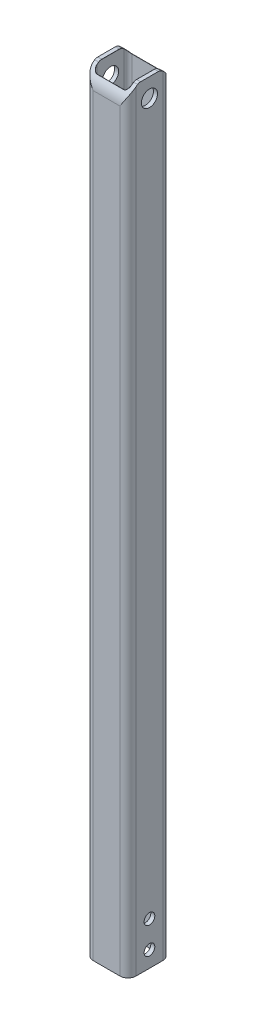
SolidWorks part; units mm, degrees
material "Plain Carbon Steel"
ref_plane "Front Plane" through (0, 0, 0) normal (0, 0, 1) x (1, 0, 0)
ref_plane "Top Plane" through (0, 0, 0) normal (0, 1, 0) x (1, 0, 0)
ref_plane "Right Plane" through (0, 0, 0) normal (1, 0, 0) x (0, 0, -1)
sketch3d "3DSketch1"
  line L0 (0, 0, 0) -> (0, 914.4, 0)
  dimension "D1" = 914.4
other "Tube (square) TS2X2X0.1875(1)"
ref_plane "Plane1" through (0, 0, 0) normal (0, 1, 0) x (1, 0, 0)
sketch "Sketch1" plane through (0, 0, 0) normal (0, 1, 0) x (1, 0, 0)
  line L0 (-15.875, -20.6375) -> (15.875, -20.6375)
  line L1 (-20.6375, -15.875) -> (-20.6375, 15.875)
  line L2 (15.875, 20.6375) -> (-15.875, 20.6375)
  line L3 (20.6375, 15.875) -> (20.6375, -15.875)
  line L4 (-15.875, -25.4) -> (15.875, -25.4)
  line L5 (-25.4, -15.875) -> (-25.4, 15.875)
  line L6 (15.875, 25.4) -> (-15.875, 25.4)
  line L7 (25.4, 15.875) -> (25.4, -15.875)
  line L8 (-25.4, 0) -> (-20.6375, 0) construction
  line L9 (-20.6375, 0) -> (20.6375, 0) construction
  line L10 (20.6375, 0) -> (25.4, 0) construction
  line L11 (0, 25.4) -> (0, 20.6375) construction
  line L12 (0, 20.6375) -> (0, -20.6375) construction
  line L13 (0, -20.6375) -> (0, -25.4) construction
  arc A0 (25.4, 15.875) -> (15.875, 25.4) centre (15.875, 15.875) ccw
  arc A1 (15.875, -25.4) -> (25.4, -15.875) centre (15.875, -15.875) ccw
  arc A2 (-25.4, -15.875) -> (-15.875, -25.4) centre (-15.875, -15.875) ccw
  arc A3 (-15.875, 25.4) -> (-25.4, 15.875) centre (-15.875, 15.875) ccw
  arc A4 (-15.875, 20.6375) -> (-20.6375, 15.875) centre (-15.875, 15.875) ccw
  arc A5 (20.6375, 15.875) -> (15.875, 20.6375) centre (15.875, 15.875) ccw
  arc A6 (15.875, -20.6375) -> (20.6375, -15.875) centre (15.875, -15.875) ccw
  arc A7 (-20.6375, -15.875) -> (-15.875, -20.6375) centre (-15.875, -15.875) ccw
  point P6 (-25.4, -25.4)
  point P33 (-25.4, 25.4)
  point P35 (25.4, 25.4)
  point P36 (25.4, -25.4)
  point P37 (0, 0)
  dimension "D1" = 9.525
  dimension "Thickness" = 4.7625
  dimension "V_leg" = 50.8
  dimension "H_leg" = 50.8
sketch "Sketch2" plane through (25.4, 0, 0) normal (1, 0, 0) x (0, 0, -1)
  line L0 (0, 914.4) -> (0, 892.175) construction
  line L1 (-15.875, 914.4) -> (15.875, 914.4) construction
  line L2 (-25.4, 914.4) -> (-25.4, 0) construction
  line L3 (-25.4, 892.175) -> (-25.4, 931.2362)
  line L4 (-25.4, 931.2362) -> (25.4, 931.2362)
  line L5 (25.4, 931.2362) -> (25.4, 892.175)
  circle A0 centre (0, 892.175) radius 9.525
  arc A1 (25.4, 892.175) -> (-25.4, 892.175) centre (0, 892.175) ccw
  dimension "D1" = 19.05
  dimension "D2" = 22.225
extrude "Cut-Extrude1" cut sketch "Sketch2" against normal through all
fillet "Fillet1" radius 6.35 4 edges at (23.0188, 914.4, -12.2967) (23.0188, 914.4, 12.2967) (-23.0188, 914.4, -12.2967) (-23.0188, 914.4, 12.2967)
fillet "Fillet2" radius 0.127 16 edges at (-18.5031, 908.0264, -19.8467) (-20.6375, 912.6928, -14.9727) (-20.6375, 914.1297, -12.3634) (-20.6375, 914.4, 0) (-20.6375, 914.1297, 12.3634) (-20.6375, 912.6928, 14.9727) (-17.4563, 907.3517, 20.3673) (0, 906.9822, 20.6375) (19.4048, 908.9503, 19.0722) (20.6375, 912.6928, 14.9727) (20.6375, 914.1297, 12.3634) (20.6375, 914.4, 0) (20.6375, 914.1297, -12.3634) (20.6375, 912.6928, -14.9727) (18.0199, 907.6688, -20.1271) (0, 906.9822, -20.6375)
sketch "Sketch3" plane through (25.4, 0, 0) normal (1, 0, 0) x (0, 0, -1)
  line L0 (0, 0) -> (0, 50.8) construction
  line L1 (-15.875, 0) -> (15.875, 0) construction
  circle A0 centre (0, 50.8) radius 6.35
  circle A1 centre (0, 19.05) radius 6.35
  dimension "D3" = 12.7
  dimension "D1" = 19.05
  dimension "D2" = 50.8
extrude "Cut-Extrude2" cut sketch "Sketch3" against normal through all
